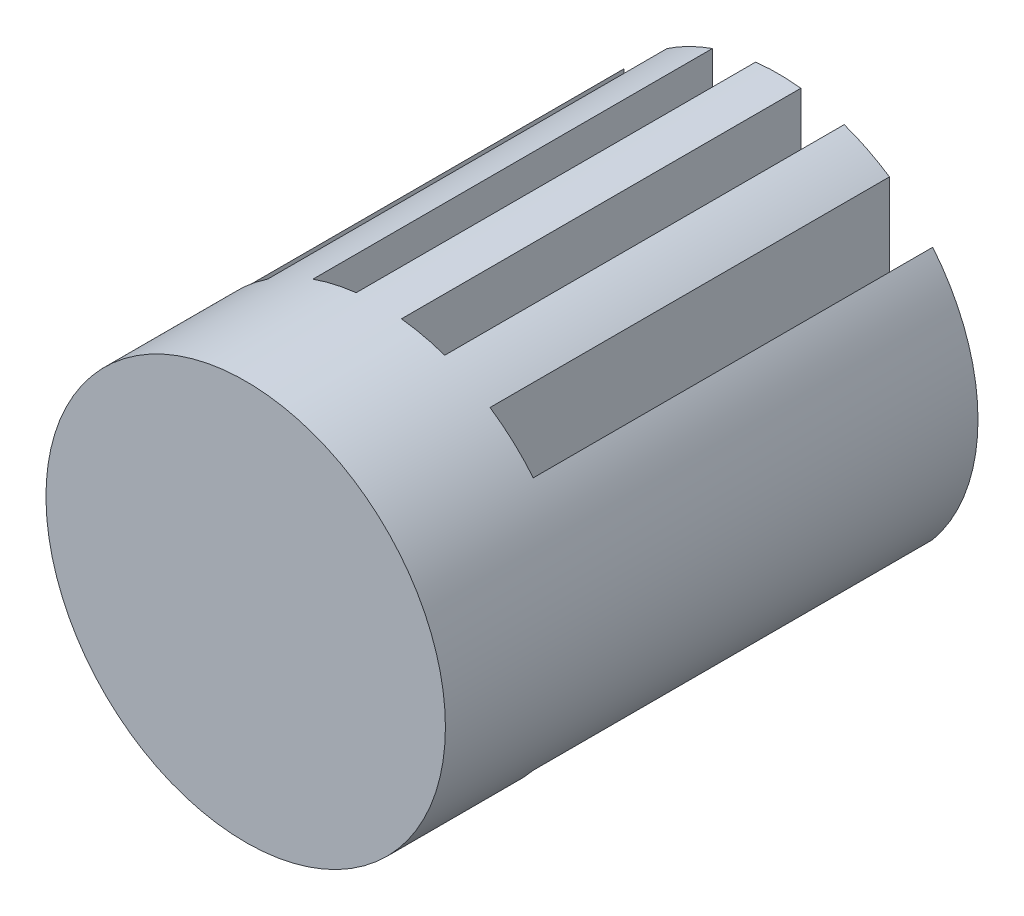
SolidWorks part; units mm, degrees
ref_plane "Plan de face" through (0, 0, 0) normal (0, 0, 1) x (1, 0, 0)
ref_plane "Plan de dessus" through (0, 0, 0) normal (0, 1, 0) x (1, 0, 0)
ref_plane "Plan de droite" through (0, 0, 0) normal (1, 0, 0) x (0, 0, -1)
sketch "Esquisse1" plane through (0, 0, 0) normal (0, 0, 1) x (1, 0, 0)
  circle A0 centre (0, 0) radius 19.05
extrude "Boss.-Extru.1" add sketch "Esquisse1" along normal blind 50.8
sketch "Esquisse6" plane through (0, 0, 0) normal (0, 0, -1) x (-1, 0, 0)
  line L1 (2.159, 19.05) -> (6.2865, 19.05)
  line L2 (2.159, 19.05) -> (2.159, -19.05)
  line L3 (2.159, -19.05) -> (6.2865, -19.05)
  line L4 (6.2865, 19.05) -> (6.2865, -19.05)
  point P4 (0, 0)
  point P5 (0, 0)
  point P6 (0, 0)
extrude "Enlèv. mat.-Extru.1" cut sketch "Esquisse6" against normal blind 38.1
sketch "Esquisse7" plane through (0, 0, 0) normal (0, 0, -1) x (-1, 0, 0)
  line L1 (-2.159, 19.05) -> (-6.2865, 19.05)
  line L2 (-2.159, 19.05) -> (-2.159, -19.05)
  line L3 (-2.159, -19.05) -> (-6.2865, -19.05)
  line L4 (-6.2865, 19.05) -> (-6.2865, -19.05)
  line L5 (-10.6045, 19.05) -> (-14.732, 19.05)
  line L6 (-10.6045, 19.05) -> (-10.6045, -19.05)
  line L7 (-10.6045, -19.05) -> (-14.732, -19.05)
  line L8 (-14.732, 19.05) -> (-14.732, -19.05)
  line L9 (10.6045, 19.05) -> (14.732, 19.05)
  line L10 (10.6045, 19.05) -> (10.6045, -19.05)
  line L11 (10.6045, -19.05) -> (14.732, -19.05)
  line L12 (14.732, 19.05) -> (14.732, -19.05)
extrude "Enlèv. mat.-Extru.2" cut sketch "Esquisse7" against normal blind 38.1
